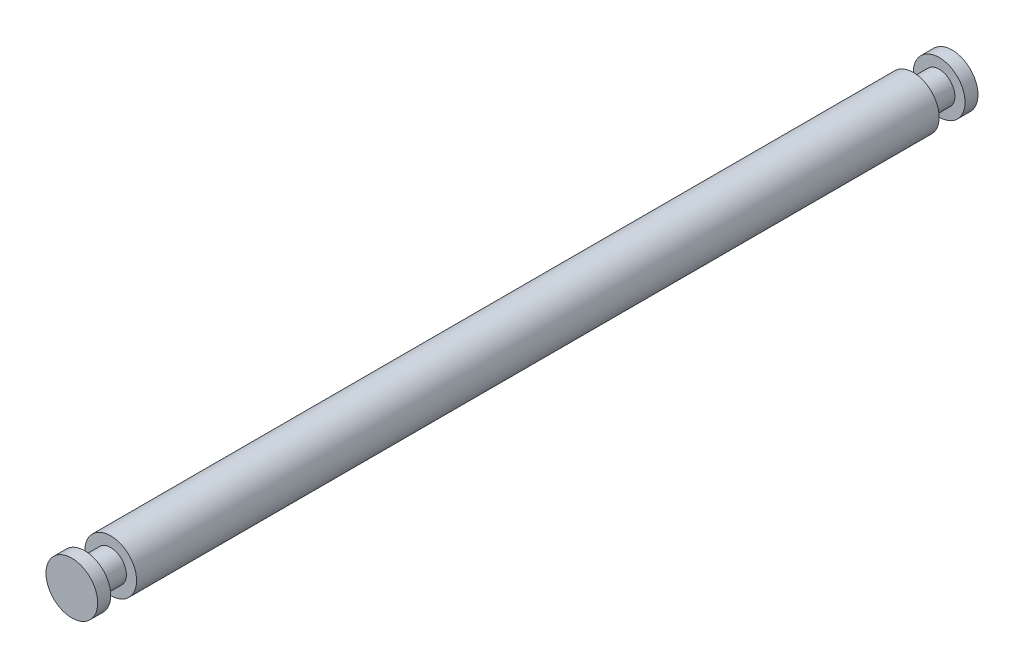
SolidWorks part; units mm, degrees
ref_plane "Front Plane" through (0, 0, 0) normal (0, 0, 1) x (1, 0, 0)
ref_plane "Top Plane" through (0, 0, 0) normal (0, 1, 0) x (1, 0, 0)
ref_plane "Right Plane" through (0, 0, 0) normal (1, 0, 0) x (0, 0, -1)
sketch "Sketch2" plane through (0, 0, 0) normal (0, 1, 0) x (1, 0, 0)
  line L1 (0, 0) -> (1.27, 0)
  line L2 (0, 0) -> (0, 43.18)
  line L3 (0, 43.18) -> (1.27, 43.18)
  line L4 (1.27, 0) -> (1.27, 43.18)
  dimension "D1" = 1.27
  dimension "D2" = 43.18
revolve "Revolve1" add sketch "Sketch2" angle 360 about L2
sketch "Sketch3" plane through (0, 0, 0) normal (0, 1, 0) x (1, 0, 0)
  line L0 (1.27, 0.635) -> (0.7706, 0.635)
  line L1 (1.27, 0) -> (1.27, 43.18) construction
  line L2 (0.7706, 0.635) -> (0.7706, 1.905)
  line L3 (0.7706, 1.905) -> (1.27, 1.905)
  line L4 (1.27, 1.905) -> (1.27, 0.635)
  line L5 (-1.27, 0) -> (1.27, 0) construction
  line L6 (0, 0) -> (0, 4.6043) construction
  dimension "D1" = 0.4994
  dimension "D2" = 0.635
  dimension "D3" = 1.27
revolve "Cut-Revolve1" cut sketch "Sketch3" angle 360 about L6
ref_plane "Mirror Point" through (0, 0, -21.59) normal (0, 0, 1) x (1, 0, 0)
mirror "Mirror1" about plane through (0, 0, -21.59) normal (0, 0, 1) of "Cut-Revolve1"
